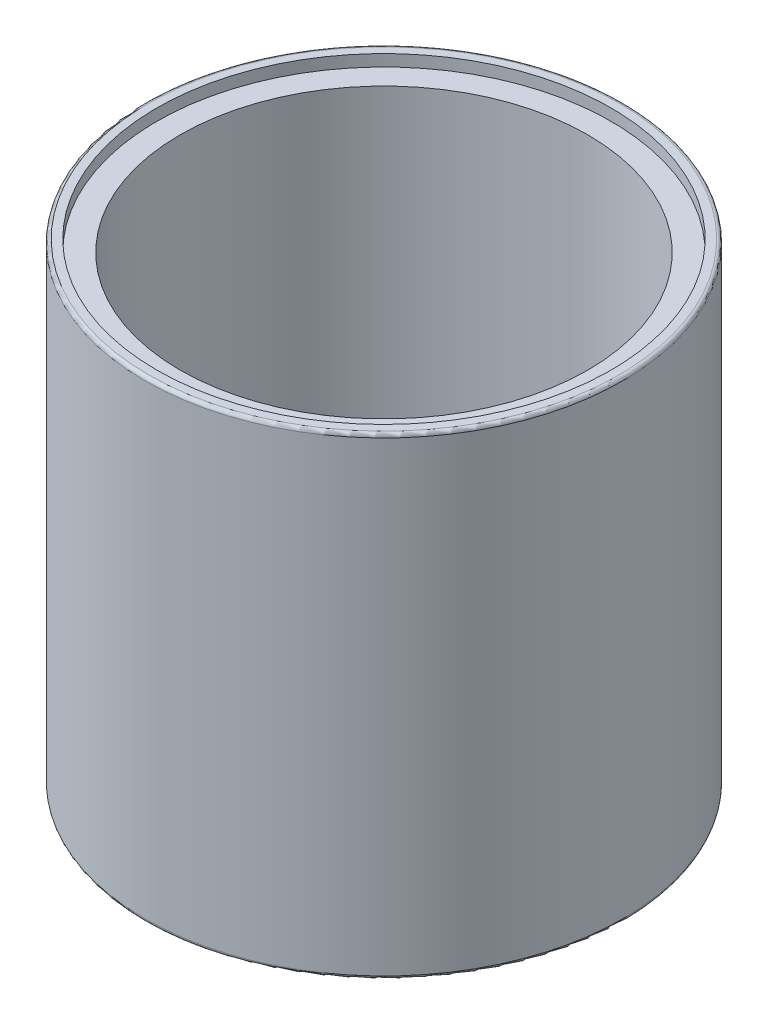
SolidWorks part; units mm, degrees
ref_plane "Front Plane" through (0, 0, 0) normal (0, 0, 1) x (1, 0, 0)
ref_plane "Top Plane" through (0, 0, 0) normal (0, 1, 0) x (1, 0, 0)
ref_plane "Right Plane" through (0, 0, 0) normal (1, 0, 0) x (0, 0, -1)
sketch "Sketch1" plane through (0, 0, 0) normal (0, 0, 1) x (1, 0, 0)
  line L0 (0, 62.3869) -> (0, -59.9327) construction
  line L1 (35, 38.6) -> (35, -38.6)
  line L2 (-29.1126, 0) -> (49.1334, 0) construction
  line L3 (35, 38.6) -> (39, 38.6)
  line L4 (39, 38.6) -> (39, 40.6)
  line L5 (39, 40.6) -> (40.4, 40.6)
  line L6 (41, 40) -> (41, -40)
  line L7 (39, -40.6) -> (40.4, -40.6)
  line L8 (39, -38.6) -> (39, -40.6)
  line L9 (35, -38.6) -> (36.5018, -38.6)
  line L10 (36.5018, -38.6) -> (36.5018, -41.2413)
  line L11 (36.5018, -41.2413) -> (38.1974, -41.2413)
  line L12 (38.1974, -41.2413) -> (38.1974, -38.6)
  line L13 (38.1974, -38.6) -> (39, -38.6)
  arc A0 (40.4, 40.6) -> (41, 40) centre (40.4, 40) cw
  arc A1 (40.4, -40.6) -> (41, -40) centre (40.4, -40) ccw
  point P16 (41, 0)
  point P19 (35, 0)
  dimension "D4" = 0.6
  dimension "D1" = 4
  dimension "D2" = 2
  dimension "D3" = 6
  dimension "D5" = 70
  dimension "D6" = 80
revolve "Revolve1" add sketch "Sketch1" angle 360 about L0
